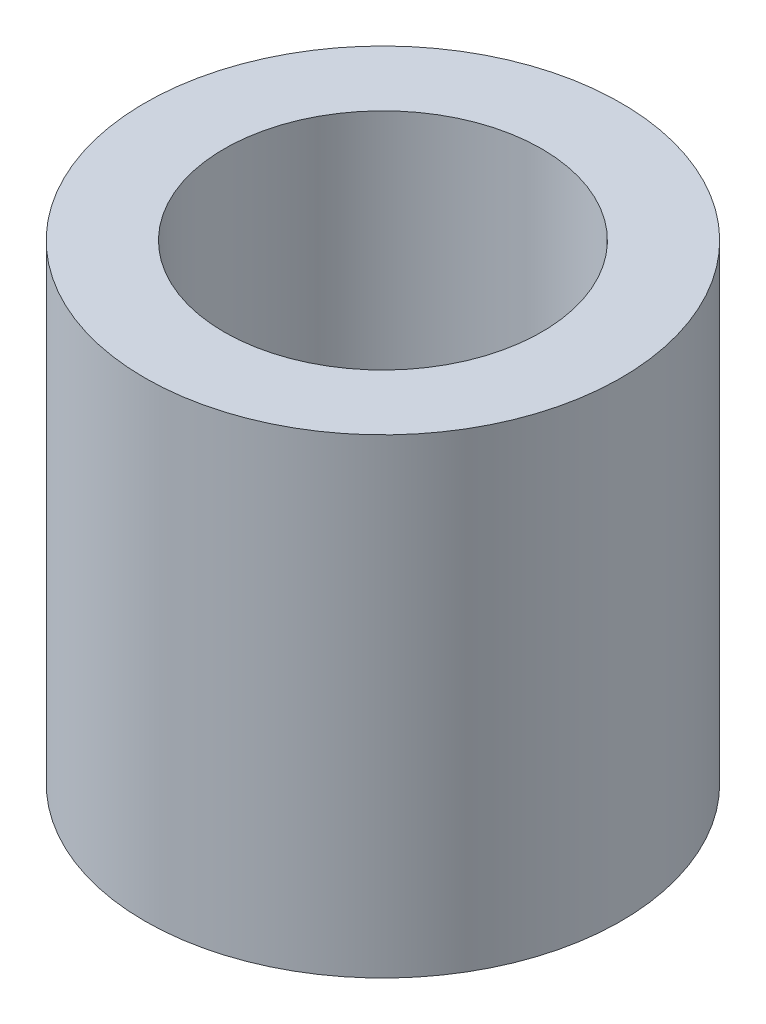
SolidWorks part; units mm, degrees
ref_plane "Front Plane" through (0, 0, 0) normal (0, 0, 1) x (1, 0, 0)
ref_plane "Top Plane" through (0, 0, 0) normal (0, 1, 0) x (1, 0, 0)
ref_plane "Right Plane" through (0, 0, 0) normal (1, 0, 0) x (0, 0, -1)
sketch "Sketch1" plane through (0, 0, 0) normal (0, 1, 0) x (1, 0, 0)
  circle A0 centre (0, 0) radius 6
  circle A1 centre (0, 0) radius 9
extrude "Boss-Extrude1" add sketch "Sketch1" along normal blind 17.78
